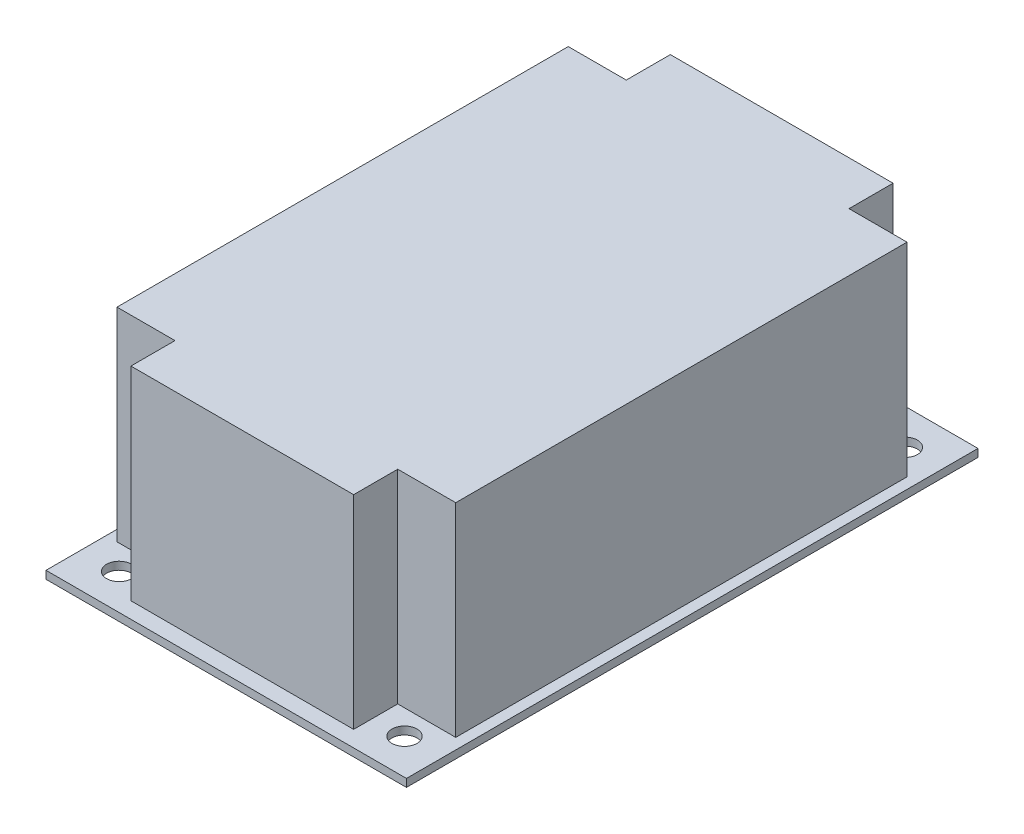
SolidWorks part; units mm, degrees
ref_plane "Front Plane" through (0, 0, 0) normal (0, 0, 1) x (1, 0, 0)
ref_plane "Top Plane" through (0, 0, 0) normal (0, 1, 0) x (1, 0, 0)
ref_plane "Right Plane" through (0, 0, 0) normal (1, 0, 0) x (0, 0, -1)
sketch "Sketch1" plane through (0, 0, 0) normal (0, 1, 0) x (1, 0, 0)
  line L1 (23.05, 36.55) -> (-23.05, 36.55)
  line L2 (23.05, 36.55) -> (23.05, -36.55)
  line L3 (23.05, -36.55) -> (-23.05, -36.55)
  line L4 (-23.05, 36.55) -> (-23.05, -36.55)
  line L5 (23.05, 36.55) -> (-23.05, -36.55) construction
  line L6 (23.05, -36.55) -> (-23.05, 36.55) construction
  point P0 (0, 0)
  dimension "D1" = 73.1
  dimension "D2" = 46.1
extrude "Boss-Extrude1" add sketch "Sketch1" along normal blind 1 contours L2 L3 L4 L1
sketch "Sketch2" plane through (0, 1, 0) normal (0, 1, 0) x (1, 0, 0)
  line L1 (14.2435, 34.496) -> (-14.2435, 34.496)
  line L2 (14.2435, 34.496) -> (14.2435, -34.496)
  line L3 (14.2435, -34.496) -> (-14.2435, -34.496)
  line L4 (-14.2435, 34.496) -> (-14.2435, -34.496)
  line L5 (14.2435, 34.496) -> (-14.2435, -34.496) construction
  line L6 (14.2435, -34.496) -> (-14.2435, 34.496) construction
  line L7 (21.662, 28.8579) -> (-21.662, 28.8579)
  line L8 (21.662, 28.8579) -> (21.662, -28.8579)
  line L9 (21.662, -28.8579) -> (-21.662, -28.8579)
  line L10 (-21.662, 28.8579) -> (-21.662, -28.8579)
  line L11 (21.662, 28.8579) -> (-21.662, -28.8579) construction
  line L12 (21.662, -28.8579) -> (-21.662, 28.8579) construction
  point P0 (0, 0)
  point P7 (0, 0)
sketch "Sketch3" plane through (0, 1, 0) normal (0, 1, 0) x (1, 0, 0)
  line L1 (18.25, 32) -> (-18.25, 32) construction
  line L2 (18.25, 32) -> (18.25, -32) construction
  line L3 (18.25, -32) -> (-18.25, -32) construction
  line L4 (-18.25, 32) -> (-18.25, -32) construction
  line L5 (18.25, 32) -> (-18.25, -32) construction
  line L6 (18.25, -32) -> (-18.25, 32) construction
  circle A0 centre (-18.25, 32) radius 1.6
  circle A1 centre (18.25, 32) radius 1.6
  circle A2 centre (18.25, -32) radius 1.6
  circle A3 centre (-18.25, -32) radius 1.6
  point P0 (0, 0)
  dimension "D3" = 3.2
  dimension "D1" = 64
  dimension "D2" = 36.5
extrude "Cut-Extrude1" cut sketch "Sketch3" against normal through all
extrude "Boss-Extrude2" add sketch "Sketch2" along normal blind 26 contours L7 L10 L9 L4 | L9 L2 L7 L4 | L7 L2 L1 L4 | L9 L8 L7 L2 | L2 L9 L4 L3
